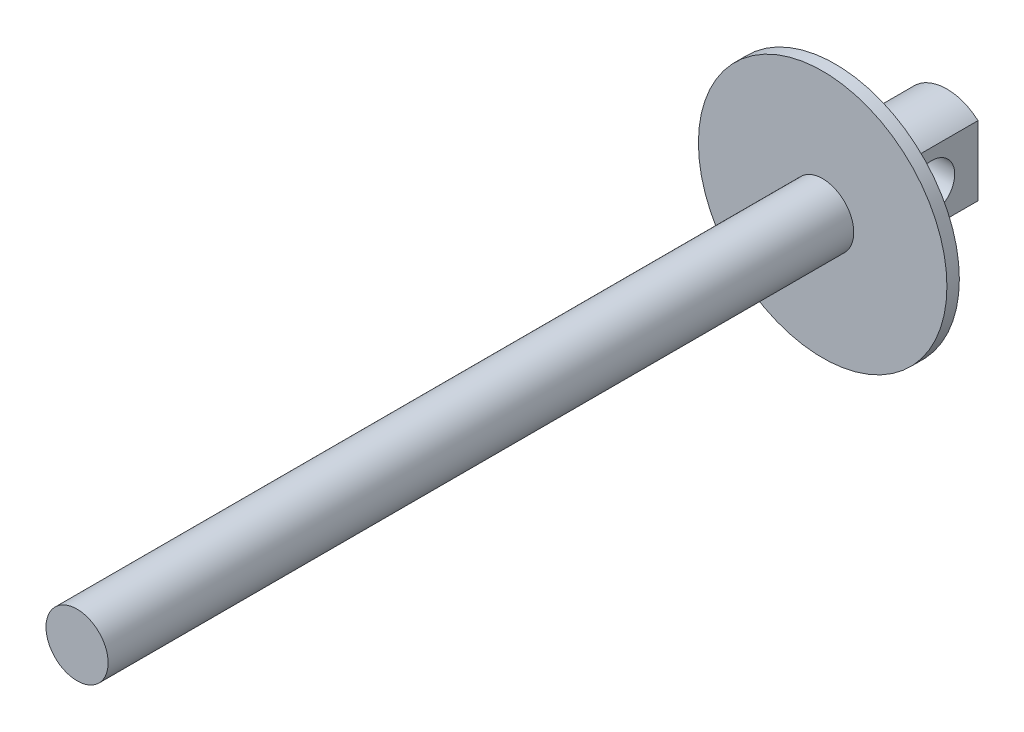
SolidWorks part; units mm, degrees
ref_plane "Front Plane" through (0, 0, 0) normal (0, 0, 1) x (1, 0, 0)
ref_plane "Top Plane" through (0, 0, 0) normal (0, 1, 0) x (1, 0, 0)
ref_plane "Right Plane" through (0, 0, 0) normal (1, 0, 0) x (0, 0, -1)
sketch "Sketch1" plane through (0, 0, 0) normal (0, 0, 1) x (1, 0, 0)
  circle A0 centre (0, 0) radius 25.4
  dimension "D1" = 50.8
extrude "Boss-Extrude1" add sketch "Sketch1" along normal blind 2.54
sketch "Sketch2" plane through (0, 0, 2.54) normal (0, 0, 1) x (1, 0, 0)
  circle A0 centre (0, 0) radius 6.35
  dimension "D1" = 12.7
extrude "Boss-Extrude2" add sketch "Sketch2" along normal blind 152.4
sketch "Sketch3" plane through (0, 0, 0) normal (0, 0, -1) x (-1, 0, 0)
  circle A0 centre (0, 0) radius 9.525
  dimension "D1" = 19.05
extrude "Boss-Extrude3" add sketch "Sketch3" along normal blind 22.86
sketch "Sketch4" plane through (0, 0, 0) normal (0, 1, 0) x (1, 0, 0)
  line L0 (0, -27.94) -> (0, 27.94) construction
  line L1 (9.525, 22.86) -> (6.35, 22.86)
  line L2 (9.525, 22.86) -> (9.525, 3.81)
  line L3 (9.525, 3.81) -> (6.35, 3.81)
  line L4 (6.35, 22.86) -> (6.35, 3.81)
  line L5 (-9.525, 22.86) -> (-6.35, 22.86)
  line L6 (-9.525, 22.86) -> (-9.525, 3.81)
  line L7 (-9.525, 3.81) -> (-6.35, 3.81)
  line L8 (-6.35, 22.86) -> (-6.35, 3.81)
  dimension "D1" = 19.05
  dimension "D2" = 19.05
  dimension "D3" = 6.35
  dimension "D4" = 6.35
extrude "Cut-Extrude2" cut sketch "Sketch4" against normal through all both and the other way through all
sketch "Sketch5" plane through (-6.35, 0, 0) normal (-1, 0, 0) x (0, 0, 1)
  line L0 (27.94, 0) -> (-27.94, 0) construction
  line L1 (-22.86, 7.0995) -> (-22.86, -7.0995) construction
  circle A0 centre (-13.335, 0) radius 4.7625
  dimension "D1" = 9.525
  dimension "D2" = 9.525
extrude "Cut-Extrude3" cut sketch "Sketch5" against normal through all both
equation "\"D4@Sketch4\"=\"D3@Sketch4\""
